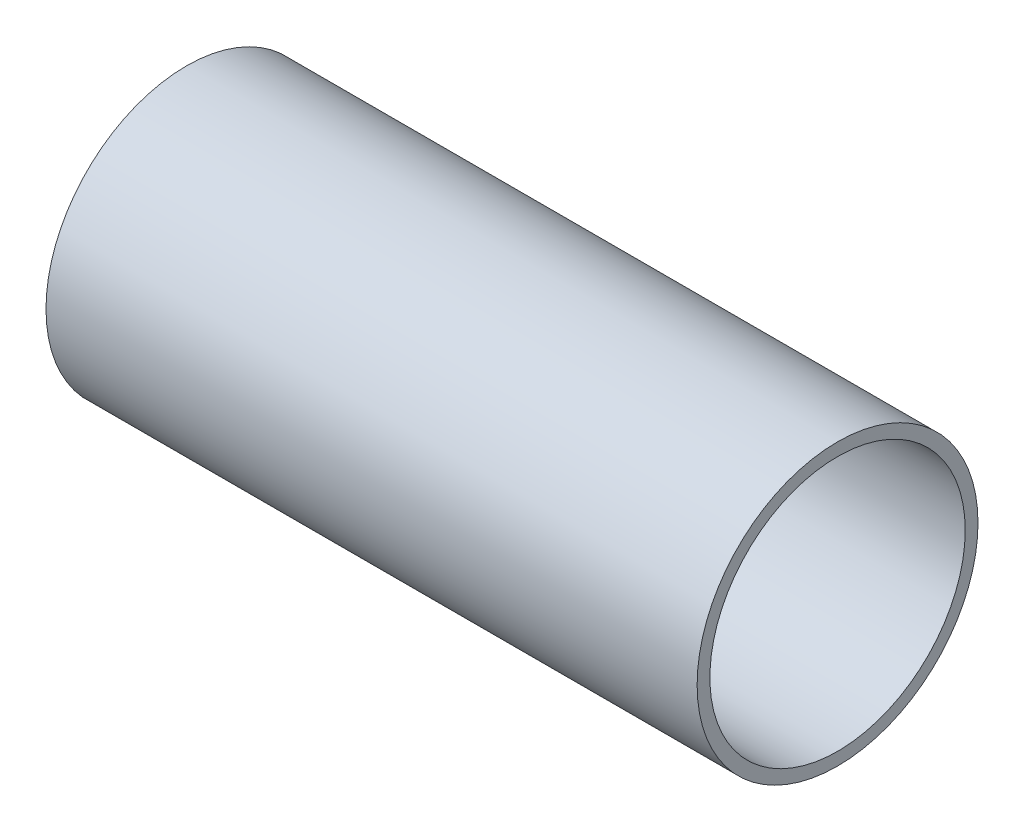
SolidWorks part; units mm, degrees
ref_plane "Front Plane" through (0, 0, 0) normal (0, 0, 1) x (1, 0, 0)
ref_plane "Top Plane" through (0, 0, 0) normal (0, 1, 0) x (1, 0, 0)
ref_plane "Right Plane" through (0, 0, 0) normal (1, 0, 0) x (0, 0, -1)
sketch "Sketch1" plane through (0, 0, 0) normal (1, 0, 0) x (0, 0, -1)
  circle A0 centre (0, 0) radius 22
  circle A1 centre (0, 0) radius 20
  dimension "D1" = 44
  dimension "D2" = 40
extrude "Boss-Extrude1" add sketch "Sketch1" along normal blind 102
